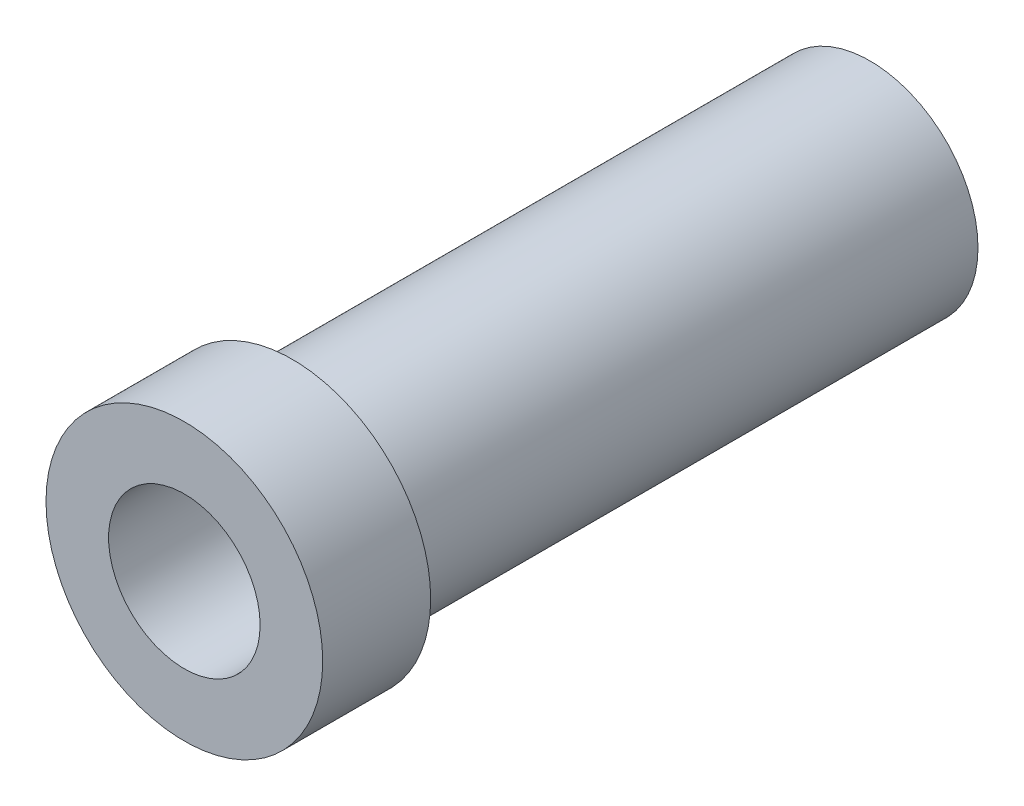
SolidWorks part; units mm, degrees
ref_plane "Front Plane" through (0, 0, 0) normal (0, 0, 1) x (1, 0, 0)
ref_plane "Top Plane" through (0, 0, 0) normal (0, 1, 0) x (1, 0, 0)
ref_plane "Right Plane" through (0, 0, 0) normal (1, 0, 0) x (0, 0, -1)
sketch "Sketch1" plane through (0, 0, 0) normal (0, 0, 1) x (1, 0, 0)
  circle A0 centre (0, 0) radius 4
  dimension "D1" = 8
extrude "Boss-Extrude1" add sketch "Sketch1" along normal mid plane 25.4
hole_wizard "#10 Clearance Hole1" positions "Sketch2" profile "Sketch3" hole size "#10" standard "ANSI Inch" end condition through all
sketch "Sketch2" plane through (0, 0, 12.7) normal (0, 0, 1) x (1, 0, 0)
  point P0 (0, 0)
sketch "Sketch3" plane through (0, 0, 12.7) normal (1, 0, 0) x (0, -1, 0)
  line L0 (0, 0) -> (0, 25.4)
  line L1 (0, 25.4) -> (2.8067, 25.4)
  line L2 (2.8067, 25.4) -> (2.8067, 0)
  line L5 (2.8067, 0) -> (0, 0)
  line L11 (0, -6.35) -> (0, 107.95) construction
  dimension "Thru Hole Dia." = 5.6134
  dimension "Thru Hole Depth" = 25.4
sketch "Sketch4" plane through (0, 0, 12.7) normal (0, 0, 1) x (1, 0, 0)
  circle A0 centre (0, 0) radius 5.125
  circle A1 centre (0, 0) radius 2.8067 construction
  circle A2 centre (0, 0) radius 2.8067
  dimension "D1" = 10.25
extrude "Boss-Extrude2" add sketch "Sketch4" against normal blind 4
sketch "Sketch5" plane through (0, 0, 12.7) normal (0, 0, 1) x (1, 0, 0)
  circle A0 centre (0, 0) radius 6.35
  circle A1 centre (0, 0) radius 2.8067 construction
  circle A2 centre (0, 0) radius 2.8067
  dimension "D1" = 12.7
extrude "Boss-Extrude3" [suppressed] add sketch "Sketch5" along normal blind 12
fillet "Fillet1" radius 0.5 1 edges at (4, 0, 8.7)
